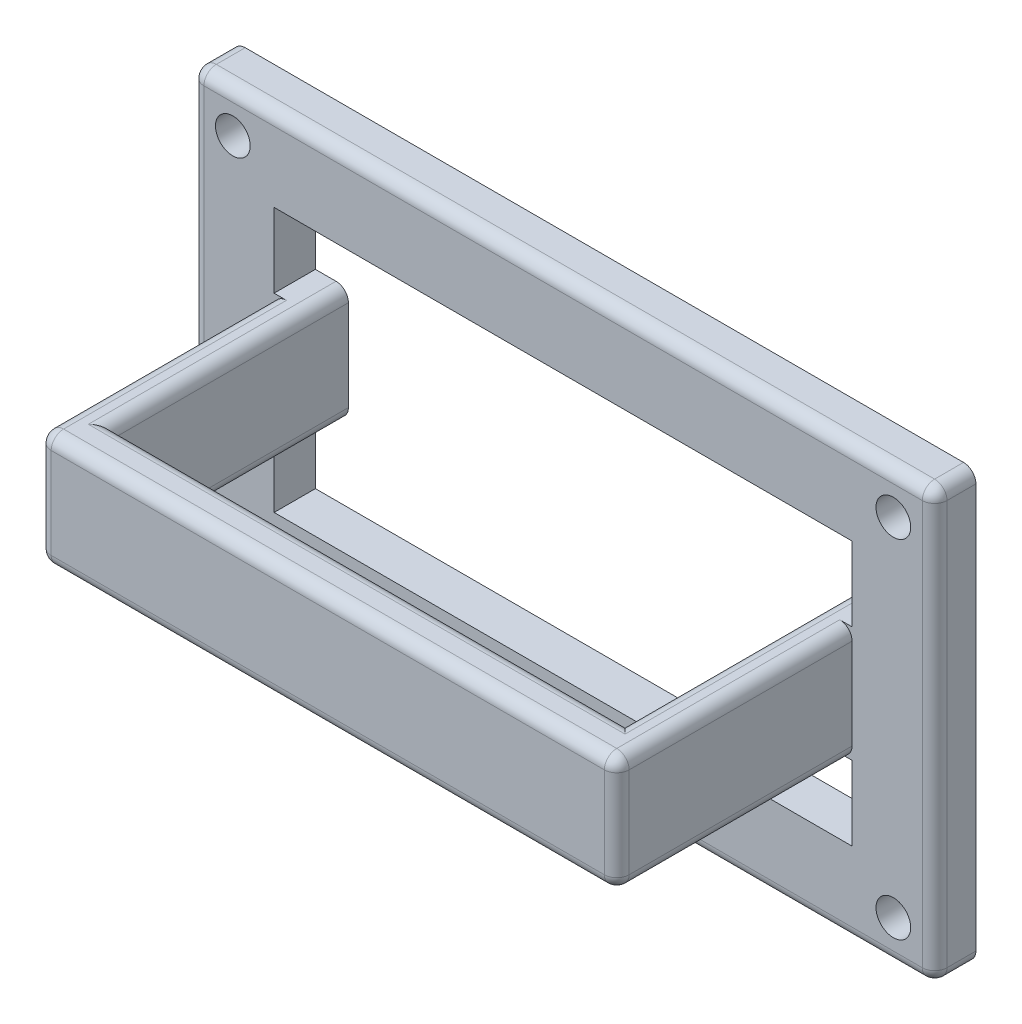
SolidWorks part; units mm, degrees
ref_plane "Front Plane" through (0, 0, 0) normal (1, 0, 0) x (0, 1, 0)
ref_plane "Top Plane" through (0, 0, 0) normal (0, 0, 1) x (0, 1, 0)
ref_plane "Right Plane" through (0, 0, 0) normal (0, 1, 0) x (-1, 0, 0)
sketch "Sketch1" plane through (0, 0, 0) normal (0, 0, 1) x (0, 1, 0)
  line L0 (26, -45) -> (26, 45)
  line L1 (16, -35) -> (-16, -35) construction
  line L2 (16, -35) -> (16, 35) construction
  line L3 (16, 35) -> (-16, 35) construction
  line L4 (-16, -35) -> (-16, 35) construction
  line L5 (16, -35) -> (-16, 35) construction
  line L6 (16, 35) -> (-16, -35) construction
  line L7 (26, 45) -> (-26, 45)
  line L8 (-26, -45) -> (-26, 45)
  line L9 (26, -45) -> (-26, -45)
  line L11 (7, -35) -> (-7, -35)
  line L12 (7, -35) -> (7, 35)
  line L13 (7, 35) -> (-7, 35)
  line L14 (-7, -35) -> (-7, 35)
  line L15 (7, -35) -> (-7, 35) construction
  line L16 (7, 35) -> (-7, -35) construction
  point P0 (0, 0)
  point P10 (0, 0)
  dimension "D1" = 70
  dimension "D2" = 32
  dimension "D4" = 14
  dimension "D3" = 10
sketch "Sketch2" plane through (0, 0, 0) normal (0, 0, 1) x (0, 1, 0)
  line L0 (7, -35) -> (7, 35) construction
  line L1 (-16, 35) -> (-7, 35)
  line L2 (-16, 35) -> (-16, -35)
  line L3 (-16, -35) -> (-7, -35)
  line L4 (16, 35) -> (16, -35)
  line L5 (-26, 45) -> (26, 45)
  line L6 (-26, 45) -> (-26, -45)
  line L7 (-26, -45) -> (26, -45)
  line L8 (26, 45) -> (26, -45)
  line L10 (-7, 35) -> (-7, 31)
  line L11 (-7, 31) -> (7, 31)
  line L12 (7, 35) -> (7, 31)
  line L13 (7, 35) -> (16, 35)
  line L15 (-7, -35) -> (-7, -31)
  line L16 (-7, -31) -> (7, -31)
  line L17 (7, -35) -> (7, -31)
  line L18 (7, -35) -> (16, -35)
  dimension "D1" = 4
  dimension "D2" = 4
extrude "Boss-Extrude1" add sketch "Sketch2" along normal blind 5
sketch "Sketch4" plane through (0, -7, 0) normal (0, -1, 0) x (1, 0, 0)
  line L0 (-35, 5) -> (-35, 33.5)
  line L1 (-31, 5) -> (-31, 28.5)
  line L2 (31, 5) -> (31, 28.5)
  line L3 (35, 5) -> (35, 33.5)
  line L4 (-35, 33.5) -> (35, 33.5)
  line L5 (-31, 28.5) -> (31, 28.5)
  line L6 (-35, 5) -> (-31, 5)
  line L7 (31, 5) -> (35, 5)
  line L8 (-31, 5) -> (-31, 0) construction
  line L9 (-31, 0) -> (-35, 0) construction
  dimension "D1" = 28.5
  dimension "D2" = 5
extrude "Boss-Extrude2" add sketch "Sketch4" along direction (0, 1, 0) on the side against the normal blind 14
sketch "Sketch8" plane through (0, 0, 5) normal (0, 0, 1) x (1, 0, 0)
  line L0 (-45, 21) -> (45, 21) construction
  line L1 (-45, 26) -> (-45, -26) construction
  line L2 (45, -26) -> (45, 26) construction
  line L3 (-40, 26) -> (-40, -26) construction
  line L4 (45, 26) -> (-45, 26) construction
  line L5 (-45, -26) -> (45, -26) construction
  line L6 (40, 26) -> (40, -26) construction
  line L7 (-45, -21) -> (45, -21) construction
  dimension "D1" = 5
  dimension "D2" = 5
  dimension "D3" = 5
  dimension "D4" = 5
hole_wizard "M5x0.8 Tapped Hole1" positions "Sketch9" profile "Sketch10" tap size "M5x0.8" standard "ANSI Metric"
sketch "Sketch9" plane through (0, 0, 5) normal (0, 0, 1) x (1, 0, 0)
  line L0 (-45, 21) -> (45, 21) construction
  line L1 (-40, 26) -> (-40, -26) construction
  line L2 (40, 26) -> (40, -26) construction
  line L3 (-45, -21) -> (45, -21) construction
  point P0 (-40, 21)
  point P6 (40, 21)
  point P10 (-40, -21)
  point P14 (40, -21)
sketch "Sketch10" plane through (-40, 21, 5) normal (1, 0, 0) x (0, -1, 0)
  line L0 (0, 0) -> (0, 8.7618)
  line L1 (0, 8.7618) -> (2.1, 7.5)
  line L2 (2.1, 7.5) -> (2.1, 0)
  line L5 (2.1, 0) -> (0, 0)
  line L10 (0, 8.7618) -> (-2.1, 7.5) construction
  line L11 (0, -6.35) -> (0, 107.95) construction
  dimension "Tap Drill Dia." = 4.2
  dimension "Tap Drill Depth" = 7.5
  dimension "Drill Angle" = 118
cosmetic thread "Hole Thread1" parameters "D1"=1.34, "D2"=5
cosmetic thread "Hole Thread2" parameters "D1"=1.34, "D2"=5
cosmetic thread "Hole Thread3" parameters "D1"=1.34, "D2"=5
cosmetic thread "Hole Thread4" parameters "D1"=1.34, "D2"=5
fillet "Fillet1" radius 1.5 22 edges at (-31, 7, 14.25) (0, 7, 28.5) (31, 7, 14.25) (31, -7, 14.25) (-31, -7, 14.25) (0, -7, 28.5) (-35, 7, 19.25) (-35, -7, 19.25) (35, 7, 19.25) (35, -7, 19.25) (-35, 0, 33.5) (0, -7, 33.5) (35, 0, 33.5) (0, 7, 33.5) (-45, -26, 2.5) (45, -26, 2.5) (-45, 26, 2.5) (45, 26, 2.5) (45, 0, 5) (0, -26, 5) (-45, 0, 5) (0, 26, 5)
